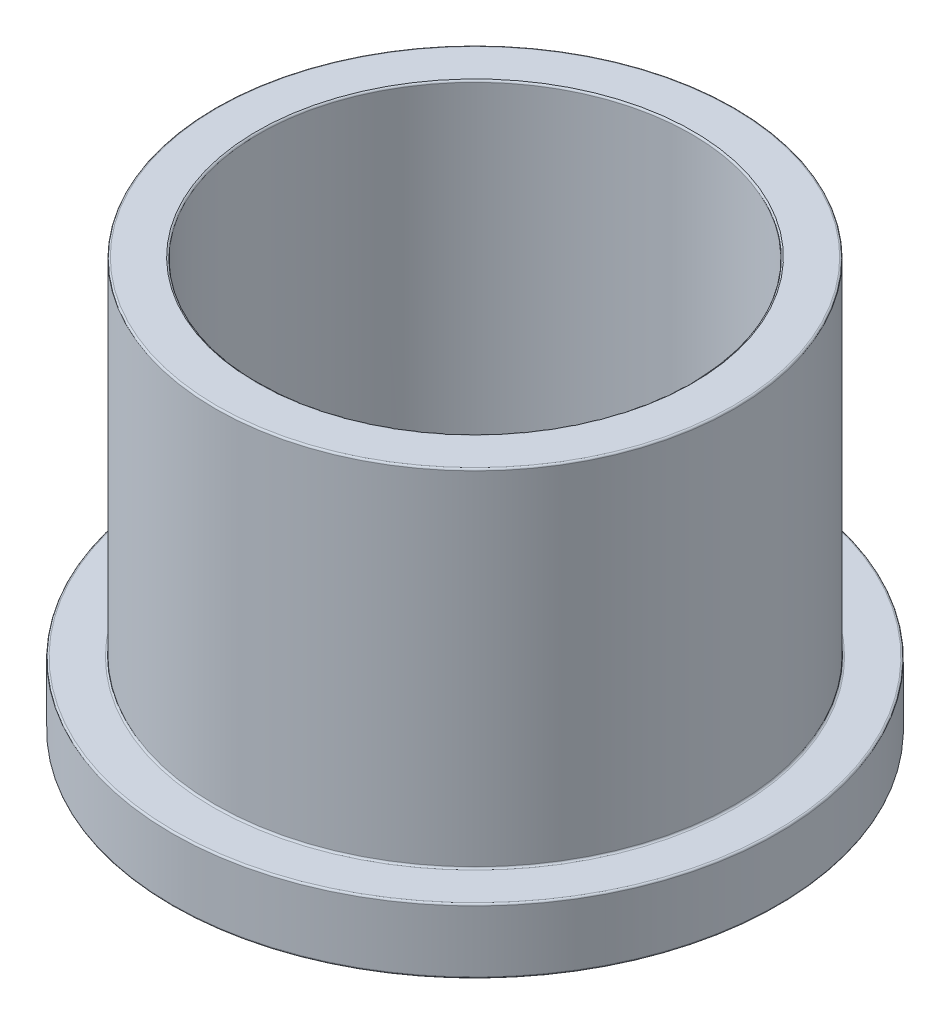
SolidWorks part; units mm, degrees
material "Brass"
ref_plane "Front Plane" through (0, 0, 0) normal (0, 0, 1) x (1, 0, 0)
ref_plane "Top Plane" through (0, 0, 0) normal (0, 1, 0) x (1, 0, 0)
ref_plane "Right Plane" through (0, 0, 0) normal (1, 0, 0) x (0, 0, -1)
sketch "Sketch1" plane through (0, 0, 0) normal (0, 0, 1) x (1, 0, 0)
  line L0 (15.875, 0) -> (0, 0) construction
  line L1 (15.875, 0) -> (15.875, 30.1625)
  line L2 (15.875, 30.1625) -> (19.05, 30.1625)
  line L3 (19.05, 30.1625) -> (19.05, 4.7625)
  line L4 (19.05, 4.7625) -> (22.225, 4.7625)
  line L5 (22.225, 4.7625) -> (22.225, 0)
  line L6 (22.225, 0) -> (15.875, 0)
  line L7 (0, 0) -> (0, 62.6366) construction
  dimension "D1" = 15.875
  dimension "D2" = 4.7625
  dimension "D3" = 19.05
  dimension "D4" = 25.4
  dimension "D5" = 22.225
revolve "Revolve1" add sketch "Sketch1" angle 360 about L7
fillet "Fillet1" radius 0.127 6 edges at (0, 0, -22.225) (0, 4.7625, -22.225) (0, 4.7625, -19.05) (0, 30.1625, -19.05) (0, 30.1625, -15.875) (0, 0, -15.875)
